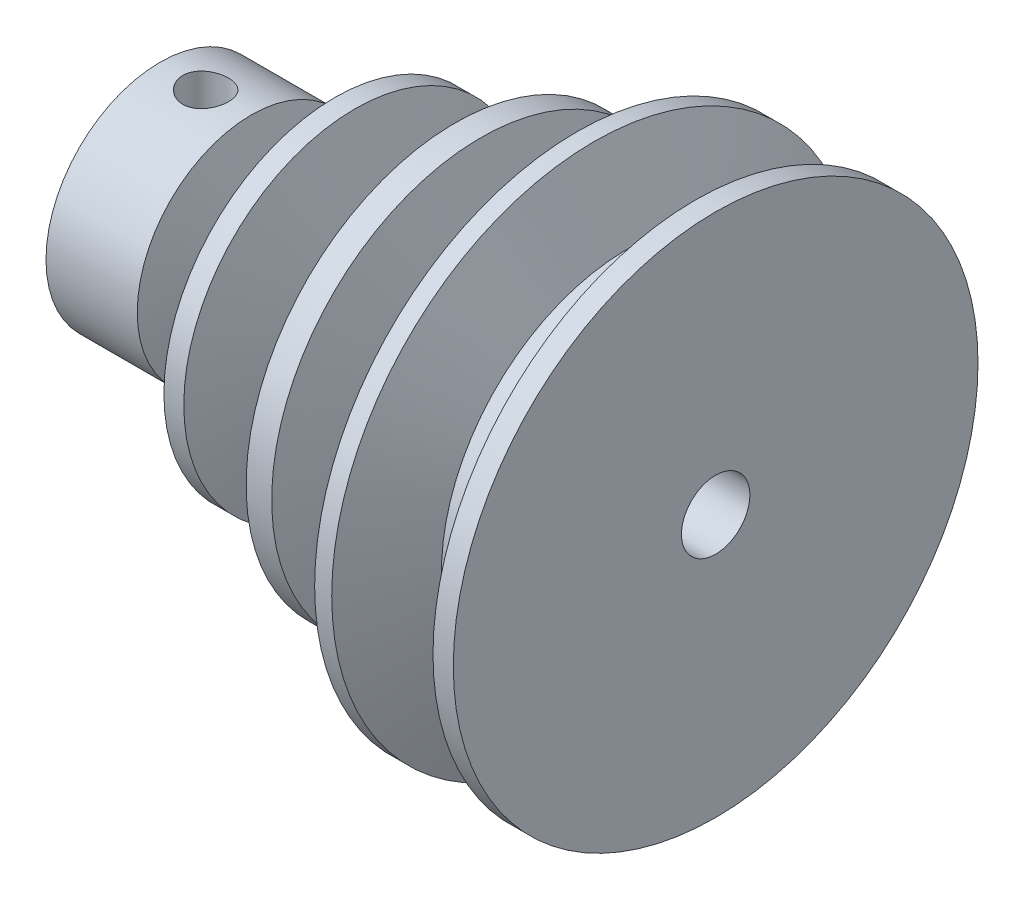
SolidWorks part; units mm, degrees
ref_plane "Front Plane" through (0, 0, 0) normal (0, 0, 1) x (1, 0, 0)
ref_plane "Top Plane" through (0, 0, 0) normal (0, 1, 0) x (1, 0, 0)
ref_plane "Right Plane" through (0, 0, 0) normal (1, 0, 0) x (0, 0, -1)
sketch "Sketch1" plane through (0, 0, 0) normal (0, 0, 1) x (1, 0, 0)
  line L0 (0, 0) -> (-73.0637, 0)
  line L1 (0, -34.5) -> (0, 34.5)
  line L2 (0, 34.5) -> (-2.6723, 34.5)
  line L3 (-2.6723, 34.5) -> (-5.5565, 24.5)
  line L4 (-5.5565, 24.5) -> (-11.5565, 24.5)
  line L5 (-11.5565, 24.5) -> (-15.9902, 34.5)
  line L6 (-15.9902, 34.5) -> (-18.2373, 34.5)
  line L7 (-18.2373, 34.5) -> (-18.2373, 27.5)
  line L8 (-18.2373, 27.5) -> (-19.9628, 27.5)
  line L9 (-19.9628, 27.5) -> (-22.3773, 18.5)
  line L10 (-22.3773, 18.5) -> (-28.3773, 18.5)
  line L11 (-28.3773, 18.5) -> (-30.8834, 27.5)
  line L12 (-30.8834, 27.5) -> (-34.2506, 27.5)
  line L13 (-34.2506, 27.5) -> (-34.2506, 22.5)
  line L14 (-34.2506, 22.5) -> (-35.976, 22.5)
  line L15 (-35.976, 22.5) -> (-38.6589, 12.5)
  line L16 (-38.6589, 12.5) -> (-44.6589, 12.5)
  line L17 (-44.6589, 12.5) -> (-47.4434, 22.5)
  line L18 (-47.4434, 22.5) -> (-50.0579, 22.5)
  line L19 (-50.0579, 22.5) -> (-50.0579, 15)
  line L20 (-50.0579, 15) -> (-51.7834, 15)
  line L21 (-51.7834, 15) -> (-53.3931, 9)
  line L22 (-53.3931, 9) -> (-59.3931, 9)
  line L23 (-59.3931, 9) -> (-61.0637, 15)
  line L24 (-61.0637, 15) -> (-73.0637, 15)
  line L25 (-61.0637, -15) -> (-73.0637, -15)
  line L26 (-59.3931, -9) -> (-61.0637, -15)
  line L27 (-73.0637, 15) -> (-73.0637, 4.5)
  line L28 (-73.0637, 4.5) -> (0, 4.5)
  line L29 (-73.0637, -4.5) -> (0, -4.5)
  line L30 (-73.0637, -15) -> (-73.0637, -4.5)
  line L31 (-22.3773, 18.5) -> (-22.3773, 35.4767) construction
  line L35 (-53.3931, -9) -> (-59.3931, -9)
  line L36 (-51.7834, -15) -> (-53.3931, -9)
  line L37 (-50.0579, -15) -> (-51.7834, -15)
  line L38 (-50.0579, -22.5) -> (-50.0579, -15)
  line L39 (-47.4434, -22.5) -> (-50.0579, -22.5)
  line L40 (-44.6589, -12.5) -> (-47.4434, -22.5)
  line L41 (-38.6589, -12.5) -> (-44.6589, -12.5)
  line L42 (-35.976, -22.5) -> (-38.6589, -12.5)
  line L43 (-34.2506, -22.5) -> (-35.976, -22.5)
  line L44 (-34.2506, -27.5) -> (-34.2506, -22.5)
  line L45 (-30.8834, -27.5) -> (-34.2506, -27.5)
  line L46 (-28.3773, -18.5) -> (-30.8834, -27.5)
  line L47 (-22.3773, -18.5) -> (-28.3773, -18.5)
  line L48 (-19.9628, -27.5) -> (-22.3773, -18.5)
  line L49 (-18.2373, -27.5) -> (-19.9628, -27.5)
  line L50 (-18.2373, -34.5) -> (-18.2373, -27.5)
  line L51 (-15.9902, -34.5) -> (-18.2373, -34.5)
  line L52 (-11.5565, -24.5) -> (-15.9902, -34.5)
  line L53 (-5.5565, -24.5) -> (-11.5565, -24.5)
  line L54 (-2.6723, -34.5) -> (-5.5565, -24.5)
  line L55 (0, -34.5) -> (-2.6723, -34.5)
  line L56 (-73.0637, 4.5) -> (-73.0637, -4.5)
  point P2 (0, 0)
  point P5 (-35.7794, 27.5)
  point P31 (-50.5709, 22.5)
  point P36 (-37.2529, 22.5)
  point P37 (-37.2758, 22.5)
  point P38 (-51.2529, 15)
  point P61 (-31.2357, 27.5)
  point P62 (-19.6695, 27.5)
  point P63 (-18.9746, 27.5)
  point P64 (-47.8348, 22.5)
  point P65 (-49.7442, 22.5)
  point P66 (-59.973, 9)
  point P67 (-75.2446, 0)
  point P68 (0, 0)
  dimension "D1" = 69
  dimension "D2" = 9
  dimension "D3" = 40
  dimension "D4" = 30
  dimension "D5" = 12
  dimension "D6" = 45
  dimension "D7" = 55
  dimension "D9" = 18
  dimension "D10" = 25
  dimension "D11" = 37
  dimension "D12" = 49
  dimension "D13" = 6
revolve "Revolve1" add sketch "Sketch1" angle 360 about L0
sketch "Sketch2" plane through (0, 0, 0) normal (0, 1, 0) x (1, 0, 0)
  line L0 (-61.0637, 15) -> (-61.0637, -15) construction
  circle A0 centre (-67.0637, 0) radius 3
  dimension "D1" = 6
  dimension "D2" = 6
extrude "Cut-Extrude1" cut sketch "Sketch2" against normal mid plane 47
